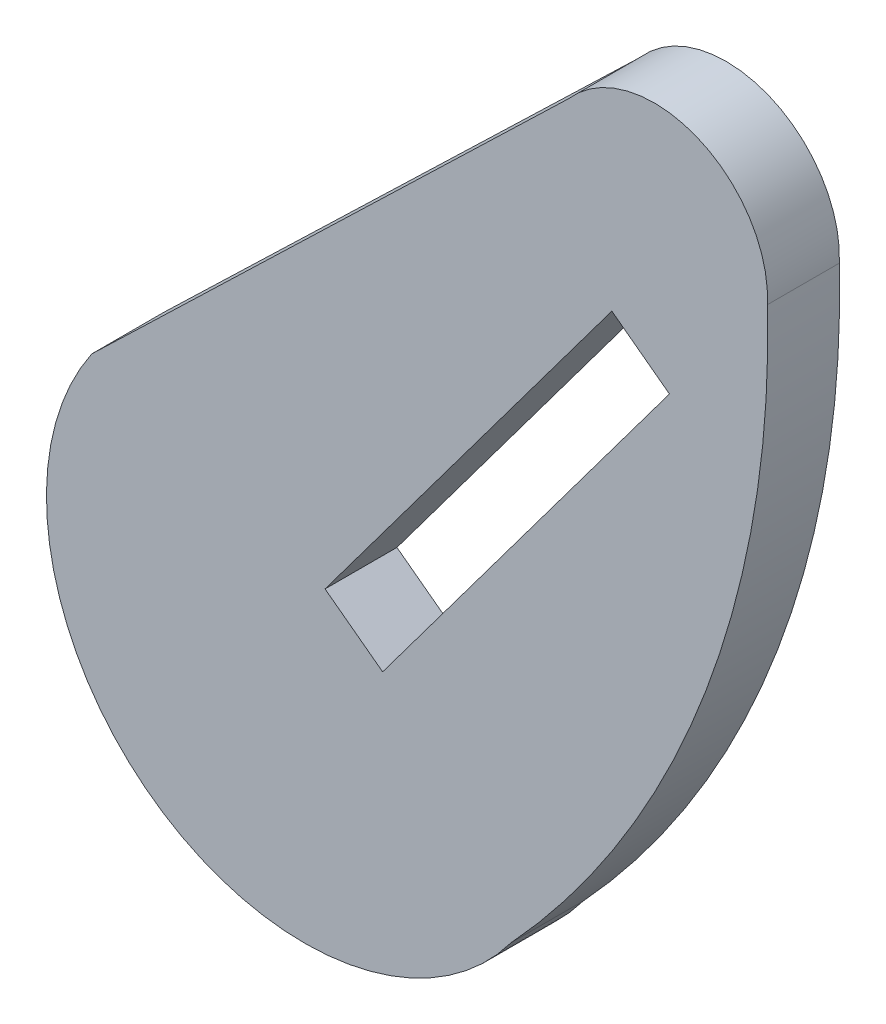
SolidWorks part; units mm, degrees
ref_plane "Front" through (0, 0, 0) normal (0, 0, 1) x (1, 0, 0)
ref_plane "Top" through (0, 0, 0) normal (0, 1, 0) x (1, 0, 0)
ref_plane "Right" through (0, 0, 0) normal (1, 0, 0) x (0, 0, -1)
sketch "Sketch1" plane through (0, 0, 0) normal (0, 0, 1) x (1, 0, 0)
  line L0 (-809.5317, -111.2297) -> (-789.6141, -92.0396)
  line L1 (-797.3908, -116.6544) -> (-785.4187, -100.624)
  line L2 (-785.4187, -100.624) -> (-787.8223, -98.8289)
  line L3 (-787.8223, -98.8289) -> (-799.7944, -114.8592)
  line L4 (-799.7944, -114.8592) -> (-797.3908, -116.6544)
  arc A0 (-809.5317, -111.2297) -> (-792.0316, -123.7697) centre (-800.658, -117.3272) ccw
  arc A1 (-792.0316, -123.7697) -> (-781.3261, -95.3477) centre (-821.6456, -96.388) ccw
  arc A2 (-781.3261, -95.3477) -> (-789.6141, -92.0396) centre (-786.0479, -95.1411) ccw
  dimension "D1" = 3
extrude "Base-Extrude" add sketch "Sketch1" along normal blind 3
